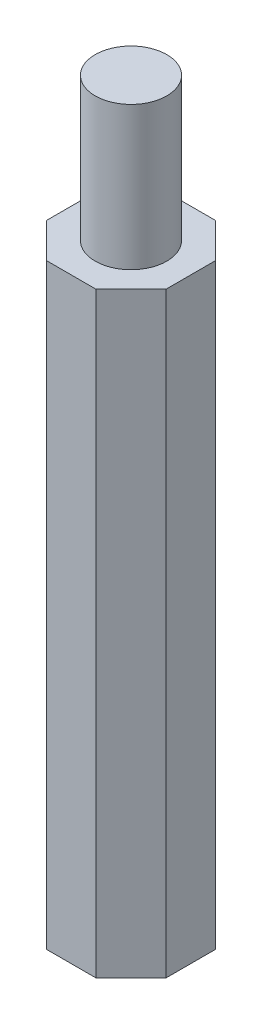
SolidWorks part; units mm, degrees
ref_plane "Plan de face" through (0, 0, 0) normal (0, 0, 1) x (1, 0, 0)
ref_plane "Plan de dessus" through (0, 0, 0) normal (0, 1, 0) x (1, 0, 0)
ref_plane "Plan de droite" through (0, 0, 0) normal (1, 0, 0) x (0, 0, -1)
sketch "Esquisse1" plane through (0, 0, 0) normal (0, 1, 0) x (1, 0, 0)
  line L0 (-1.0355, 2.5) -> (1.0355, 2.5)
  line L1 (1.0355, 2.5) -> (2.5, 1.0355)
  line L2 (2.5, 1.0355) -> (2.5, -1.0355)
  line L3 (2.5, -1.0355) -> (1.0355, -2.5)
  line L4 (1.0355, -2.5) -> (-1.0355, -2.5)
  line L5 (-1.0355, -2.5) -> (-2.5, -1.0355)
  line L6 (-2.5, -1.0355) -> (-2.5, 1.0355)
  line L7 (-2.5, 1.0355) -> (-1.0355, 2.5)
  line L8 (0, 2.5) -> (0, -2.5) construction
  dimension "D1" = 5
extrude "Extrusion1" add sketch "Esquisse1" along normal mid plane 25
sketch "Esquisse2" plane through (0, 12.5, 0) normal (0, 1, 0) x (1, 0, 0)
  circle A0 centre (0, 0) radius 1.5
  dimension "D1" = 3
extrude "Extrusion2" add sketch "Esquisse2" along normal blind 6
sketch "Esquisse3" plane through (0, -12.5, 0) normal (0, -1, 0) x (1, 0, 0)
  circle A0 centre (0, 0) radius 1.5
  dimension "D1" = 3
extrude "Enlèv. mat.-Extru.1" cut sketch "Esquisse3" against normal blind 7
